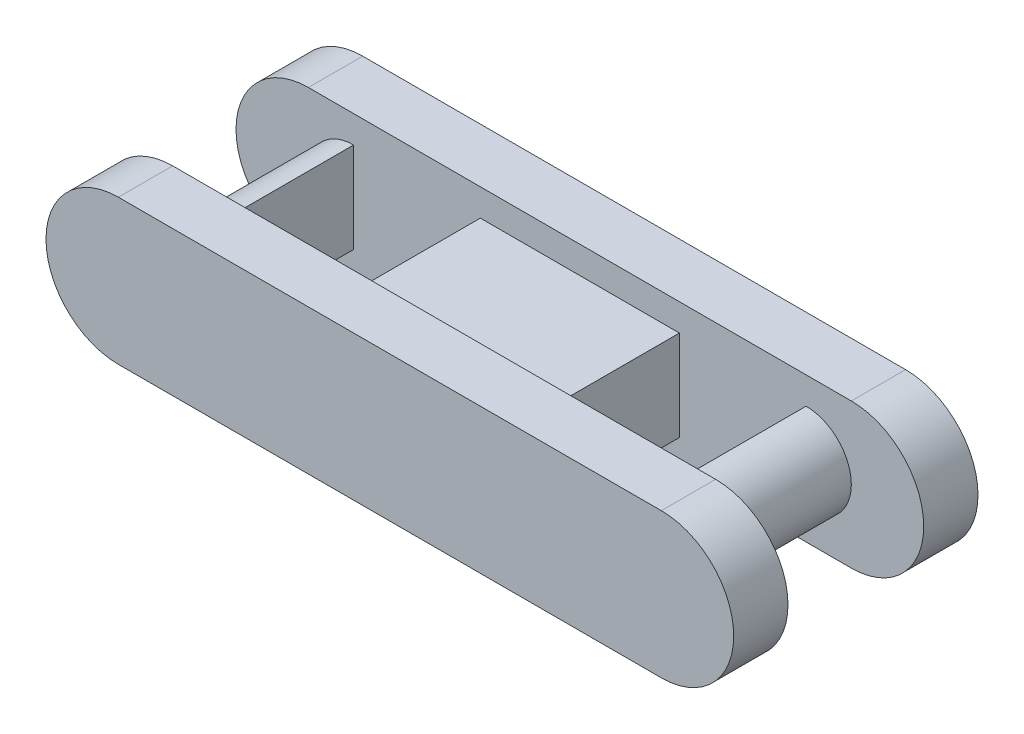
SolidWorks part; units mm, degrees
material "PE High Density"
ref_plane "Front Plane" through (0, 0, 0) normal (0, 0, 1) x (1, 0, 0)
ref_plane "Top Plane" through (0, 0, 0) normal (0, 1, 0) x (1, 0, 0)
ref_plane "Right Plane" through (0, 0, 0) normal (1, 0, 0) x (0, 0, -1)
sketch "Sketch1" plane through (0, 0, 0) normal (0, 0, 1) x (1, 0, 0)
  line L1 (-15, 4) -> (15, 4)
  line L3 (-15, -4) -> (15, -4)
  line L5 (-15, 4) -> (15, -4) construction
  line L6 (-15, -4) -> (15, 4) construction
  arc A0 (-15, 4) -> (-15, -4) centre (-15, 0) ccw
  arc A2 (15, -4) -> (15, 4) centre (15, 0) ccw
  point P0 (0, 0)
  dimension "D3" = 8
  dimension "D4" = 8
  dimension "D5" = 30
  dimension "D6" = 15
  dimension "D1" = 8
  dimension "D2" = 30
extrude "Boss-Extrude1" add sketch "Sketch1" along normal blind 3
sketch "Sketch4" plane through (0, 0, 3) normal (0, 0, 1) x (1, 0, 0)
  line L1 (-12.5, 2.5) -> (12.5, 2.5)
  line L3 (-12.5, -2.5) -> (12.5, -2.5)
  arc A0 (-12.5, 2.5) -> (-12.5, -2.5) centre (-12.5, 0) ccw
  arc A1 (12.5, -2.5) -> (12.5, 2.5) centre (12.5, 0) ccw
  point P0 (0, 0)
  dimension "D3" = 5
  dimension "D4" = 5
  dimension "D7" = 25
  dimension "D1" = 25
  dimension "D2" = 5
  dimension "D5" = 12.5
  dimension "D6" = 12.5
  dimension "D8" = 2.5
extrude "Boss-Extrude2" add sketch "Sketch4" along normal blind 7.5
sketch "Sketch5" plane through (0, 2.5, 0) normal (0, 1, 0) x (1, 0, 0)
  line L0 (-12.5, -6.75) -> (12.5, -6.75) construction
  line L1 (-12.5, -10.5) -> (-12.5, -3) construction
  line L2 (12.5, -10.5) -> (12.5, -3) construction
ref_plane "Plane1" through (0, 0, 6.75) normal (0, 0, 1) x (1, 0, 0)
mirror "Mirror1" about plane through (0, 0, 6.75) normal (0, 0, 1) of "Boss-Extrude1"
sketch "Sketch6" plane through (0, 2.5, 0) normal (0, 1, 0) x (1, 0, 0)
  line L0 (12.5, -10.5) -> (-12.5, -10.5) construction
  line L1 (-12.5, -3) -> (-5.5, -3)
  line L2 (-12.5, -3) -> (-12.5, -10.5)
  line L3 (-12.5, -10.5) -> (-5.5, -10.5)
  line L4 (-5.5, -3) -> (-5.5, -10.5)
  line L6 (12.5, -3) -> (5.5, -3)
  line L7 (12.5, -3) -> (12.5, -10.5)
  line L8 (12.5, -10.5) -> (5.5, -10.5)
  line L9 (5.5, -3) -> (5.5, -10.5)
  dimension "D1" = 7
  dimension "D2" = 7
extrude "Cut-Extrude1" cut sketch "Sketch6" against normal blind 7.5
